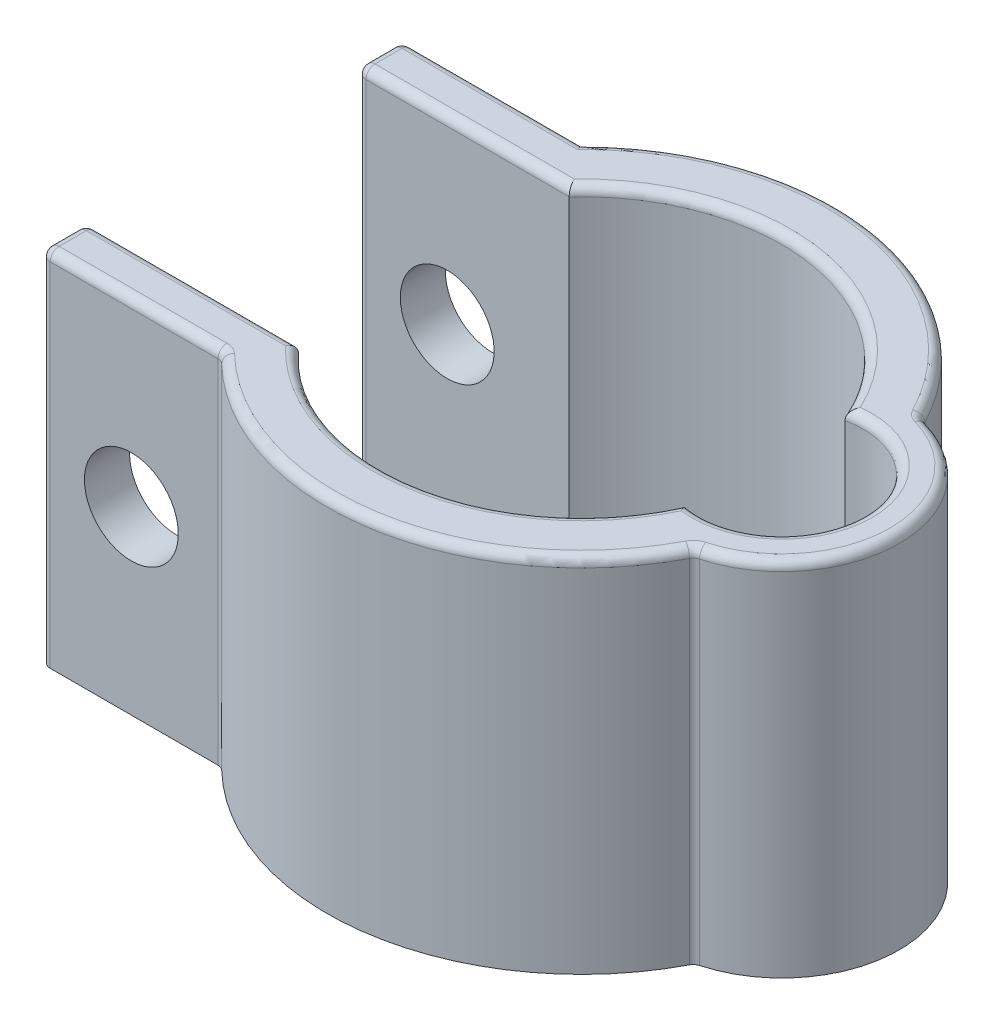
SolidWorks part; units mm, degrees
ref_plane "Plan de face" through (0, 0, 0) normal (0, 0, 1) x (1, 0, 0)
ref_plane "Plan de dessus" through (0, 0, 0) normal (0, 1, 0) x (1, 0, 0)
ref_plane "Plan de droite" through (0, 0, 0) normal (1, 0, 0) x (0, 0, -1)
sketch "Esquisse1" plane through (0, 0, 0) normal (0, 1, 0) x (1, 0, 0)
  line L0 (-8.1829, 7.5) -> (-19.9403, 7.5)
  line L1 (-19.9403, 7.5) -> (-19.9403, 10)
  line L2 (-19.9403, 10) -> (-9.9403, 10)
  line L3 (0, 0) -> (-11.1, 0) construction
  line L4 (-8.1829, -7.5) -> (-19.9403, -7.5)
  line L5 (-19.9403, -7.5) -> (-19.9403, -10)
  line L6 (-19.9403, -10) -> (-9.9403, -10)
  arc A0 (-8.1829, -7.5) -> (10.1878, -4.4066) centre (0, 0) ccw
  arc A1 (-9.9403, -10) -> (12.6023, -6.324) centre (0, 0) ccw
  arc A2 (10.1878, -4.4066) -> (10.1878, 4.4066) centre (11.1, 0) ccw
  arc A3 (12.6023, -6.324) -> (12.6023, 6.324) centre (11.1, 0) ccw
  arc A4 (10.1878, 4.4066) -> (-8.1829, 7.5) centre (0, 0) ccw
  arc A5 (12.6023, 6.324) -> (-9.9403, 10) centre (0, 0) ccw
  dimension "D1" = 22.2
  dimension "D2" = 3
  dimension "D3" = 9
  dimension "D4" = 2
  dimension "D5" = 2.5
  dimension "D6" = 10
  dimension "D7" = 15
extrude "Boss.-Extru.1" add sketch "Esquisse1" along normal blind 20
sketch "Esquisse2" plane through (0, 0, -10) normal (0, 0, -1) x (-1, 0, 0)
  line L0 (19.9403, 10) -> (9.9403, 10) construction
  line L1 (19.9403, 20) -> (19.9403, 0) construction
  line L2 (9.9403, 20) -> (9.9403, 0) construction
  line L3 (14.9403, 20) -> (14.9403, 0) construction
  line L4 (9.9403, 20) -> (19.9403, 20) construction
  line L5 (9.9403, 0) -> (19.9403, 0) construction
  circle A0 centre (14.9403, 10) radius 2.6
  point P12 (14.9403, 10)
  dimension "D1" = 5.2
extrude "Enlèv. mat.-Extru.1" cut sketch "Esquisse2" against normal through all
fillet "Congé2" radius 0.5 19 edges at (-14.0616, 20, 7.5) (1.8432, 20, 10.9459) (15.6, 20, 0) (-14.9403, 20, -10) (-14.0616, 20, -7.5) (1.8432, 20, -10.9459) (2.2693, 20, -13.9162) (17.6, 20, 0) (2.2693, 20, 13.9162) (-14.9403, 20, 10) (-19.9403, 20, 8.75) (-19.9403, 20, -8.75) (-19.9403, 10, 10) (-19.9403, 10, 7.5) (-19.9403, 10, -7.5) (-19.9403, 10, -10) (12.6023, 10, -6.324) (12.6023, 10, 6.324) (-9.9403, 10, 10)
